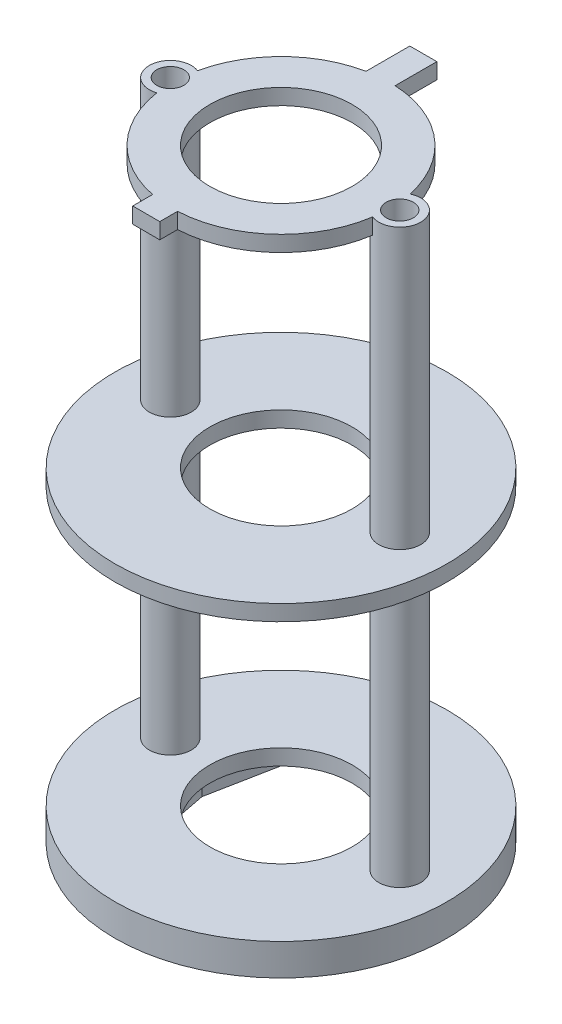
SolidWorks part; units mm, degrees
material "ABS"
ref_plane "Front Plane" through (0, 0, 0) normal (0, 0, 1) x (1, 0, 0)
ref_plane "Top Plane" through (0, 0, 0) normal (0, 1, 0) x (1, 0, 0)
ref_plane "Right Plane" through (0, 0, 0) normal (1, 0, 0) x (0, 0, -1)
sketch "Sketch1" plane through (0, 0, 0) normal (0, 1, 0) x (1, 0, 0)
  line L0 (-2.7432, 13.4907) -> (-2.7432, 19.0271)
  line L1 (-2.7432, 19.0271) -> (0.6742, 19.0271)
  line L2 (0.6742, 19.0271) -> (0.6742, 13.7503)
  line L3 (0.6742, -13.7503) -> (0.6742, -15.9995)
  line L4 (0.6742, -15.9995) -> (-2.7432, -15.9995)
  line L5 (-2.7432, -15.9995) -> (-2.7432, -13.4907)
  line L18 (0.6742, 13.7503) -> (0.6742, 19.0271) construction
  line L19 (0.6742, 19.0271) -> (-2.7432, 19.0271) construction
  line L20 (-2.7432, 19.0271) -> (-2.7432, 13.4907) construction
  line L21 (-2.7432, -13.4907) -> (-2.7432, -15.9995) construction
  line L22 (-2.7432, -15.9995) -> (0.6742, -15.9995) construction
  line L23 (0.6742, -15.9995) -> (0.6742, -13.7503) construction
  arc A0 (-13.4568, 2.9049) -> (-13.6072, -2.0901) centre (-14.4272, 0.4343) ccw
  arc A1 (13.615, -2.0385) -> (13.4695, 2.8454) centre (14.5796, 0.4343) ccw
  arc A2 (-13.6072, -2.0901) -> (-2.7432, -13.4907) centre (0, 0) ccw
  arc A3 (0.6742, -13.7503) -> (13.615, -2.0385) centre (0, 0) ccw
  arc A4 (13.4695, 2.8454) -> (0.6742, 13.7503) centre (0, 0) ccw
  arc A5 (-2.7432, 13.4907) -> (-13.4568, 2.9049) centre (0, 0) ccw
  arc A18 (-2.7432, 13.4907) -> (-13.4568, 2.9049) centre (0, 0) ccw construction
  arc A19 (-13.4568, 2.9049) -> (-13.6072, -2.0901) centre (-14.4272, 0.4343) ccw construction
  arc A20 (-13.6072, -2.0901) -> (-2.7432, -13.4907) centre (0, 0) ccw construction
  arc A21 (0.6742, -13.7503) -> (13.615, -2.0385) centre (0, 0) ccw construction
  arc A22 (13.615, -2.0385) -> (13.4695, 2.8454) centre (14.5796, 0.4343) ccw construction
  arc A23 (13.4695, 2.8454) -> (0.6742, 13.7503) centre (0, 0) ccw construction
extrude "Boss-Extrude1" add sketch "Sketch1" against normal blind 2 contours A5 A0 A2 L5 L4 L3 A3 A1 A4 L2 L1 L0
sketch "Sketch2" plane through (0, 0, 0) normal (0, 1, 0) x (1, 0, 0)
  circle A0 centre (-14.4272, 0.4343) radius 2.6543
  circle A1 centre (14.5796, 0.4343) radius 2.6543
  circle A2 centre (14.5796, 0.4343) radius 1.7145
  circle A3 centre (-14.4272, 0.4343) radius 1.7145
  dimension "D1" = 3.429
  dimension "D2" = 3.429
extrude "Cut-Extrude1" cut sketch "Sketch2" against normal up to next contours A2 | A3
sketch "Sketch3" plane through (0, -2, 0) normal (0, -1, 0) x (1, 0, 0)
  circle A0 centre (-14.4272, -0.4343) radius 2.6543
  circle A1 centre (-14.4272, -0.4343) radius 1.7145
  circle A2 centre (14.5796, -0.4343) radius 2.6543
  circle A3 centre (14.5796, -0.4343) radius 1.7145
  circle M1 centre (-14.4272, -0.4343) radius 1.7145
  circle M2 centre (14.5796, -0.4343) radius 1.7145
  arc M7 (13.4695, -2.8454) -> (13.615, 2.0385) centre (14.5796, -0.4343) ccw
  arc M13 (-13.6072, 2.0901) -> (-13.4568, -2.9049) centre (-14.4272, -0.4343) ccw
extrude "Boss-Extrude2" add sketch "Sketch3" along normal blind 72.305 contours A2 M7 M2 | A0 M13 M1
sketch "Sketch4" plane through (0, -2, 0) normal (0, -1, 0) x (1, 0, 0)
  circle A0 centre (0, 0) radius 8.99
  arc A1 (13.615, 2.0385) -> (0.6742, 13.7503) centre (0, 0) ccw construction
  dimension "D1" = 17.98
extrude "Cut-Extrude2" cut sketch "Sketch4" against normal up to next
sketch "Sketch5" plane through (0, -74.305, 0) normal (0, -1, 0) x (1, 0, 0)
  circle A0 centre (0, 0) radius 21
  circle A1 centre (0, 0) radius 8.99
  dimension "D1" = 42
extrude "Boss-Extrude3" add sketch "Sketch5" along normal blind 2 and the other way blind 2
sketch "Sketch6" plane through (0, -76.305, 0) normal (0, -1, 0) x (1, 0, 0)
  line L0 (0, 0) -> (-7.35, 0) construction
  line L8 (-7.35, 13.65) -> (-10, 0)
  line L9 (-10, 0) -> (-7.35, -13.65)
  line L10 (7.35, -13.65) -> (10, 0)
  line L11 (10, 0) -> (7.35, 13.65)
  circle A0 centre (0, 0) radius 21
  arc A1 (-7.35, 13.65) -> (7.35, 13.65) centre (0, 0.0035) cw
  arc A2 (-7.35, -13.65) -> (7.35, -13.65) centre (0, -0.0035) ccw
  dimension "D5" = 15.5
  dimension "D6" = 15.5
  dimension "D1" = 14.7
  dimension "D2" = 27.3
  dimension "D3" = 10
  dimension "D4" = 10
extrude "Cut-Extrude3" cut sketch "Sketch6" against normal blind 2 contours A1 L11 L10 A2 L9 L8
ref_plane "Plane1" through (0, -37.305, 0) normal (0, 1, 0) x (1, 0, 0)
sketch "Sketch7" plane through (0, -37.305, 0) normal (0, 1, 0) x (1, 0, 0)
  circle A0 centre (0, 0) radius 21
  circle A1 centre (0, 0) radius 8.99
extrude "Boss-Extrude4" add sketch "Sketch7" along normal blind 2
ref_plane "Plane2" through (0, -15, 0) normal (0, 1, 0) x (1, 0, 0)
sketch "Sketch8" plane through (0, -72.305, 0) normal (0, 1, 0) x (1, 0, 0)
  circle A0 centre (-14.4272, 0.4343) radius 1.7145
  circle A1 centre (14.5796, 0.4343) radius 1.7145
extrude "Boss-Extrude5" add sketch "Sketch8" along normal up to surface (57.305 mm away)
